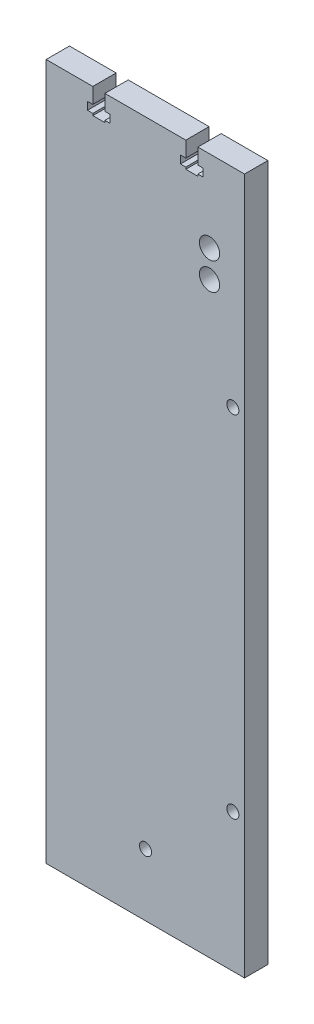
SolidWorks part; units mm, degrees
ref_plane "Płaszczyzna przednia" through (0, 0, 0) normal (0, 0, 1) x (1, 0, 0)
ref_plane "Płaszczyzna górna" through (0, 0, 0) normal (0, 1, 0) x (1, 0, 0)
ref_plane "Płaszczyzna prawa" through (0, 0, 0) normal (1, 0, 0) x (0, 0, -1)
sketch "Szkic1" plane through (0, 0, 0) normal (0, 0, 1) x (1, 0, 0)
  line L0 (23.5057, -200) -> (74.5057, -200)
  line L1 (23.5057, -200) -> (23.5057, -21)
  line L2 (74.5057, -200) -> (74.5057, -21)
  line L3 (23.5057, -21) -> (74.5057, -21)
  dimension "D2" = 51
  dimension "D3" = 179
extrude "Dodanie-wyciągnięcie1" add sketch "Szkic1" against normal blind 6
sketch "Szkic2" plane through (0, 0, -6) normal (0, 0, -1) x (-1, 0, 0)
  line L0 (-68.5057, -166) -> (-74.5057, -166) construction
  line L1 (-68.5057, -166) -> (-74.5057, -166)
  line L2 (-68.5057, -162.9) -> (-74.5057, -162.9) construction
  line L3 (-68.5057, -72.9) -> (-74.5057, -72.9) construction
  line L4 (-23.5057, -200) -> (-23.5057, -21)
  line L5 (-23.5057, -21) -> (-74.5057, -21)
  line L6 (-74.5057, -21) -> (-74.5057, -200)
  line L7 (-74.5057, -200) -> (-23.5057, -200)
  line L8 (-23.5057, -200) -> (-23.5057, -21)
  line L9 (-23.5057, -21) -> (-74.5057, -21)
  line L10 (-74.5057, -21) -> (-74.5057, -200)
  line L11 (-74.5057, -200) -> (-23.5057, -200)
  line L12 (-68.5057, -76) -> (-74.5057, -76) construction
  line L13 (-68.5057, -162.9) -> (-74.5057, -162.9)
  line L14 (-68.5057, -72.9) -> (-74.5057, -72.9)
  line L15 (-68.5057, -76) -> (-74.5057, -76)
  line L16 (-71.5057, -166) -> (-71.5057, -162.9)
  line L17 (-71.5057, -76) -> (-71.5057, -72.9)
  circle A0 centre (-71.5057, -74.45) radius 1.55
  circle A1 centre (-71.5057, -164.45) radius 1.55
  dimension "D2" = 3.1
  dimension "D3" = 3.1
  dimension "D1" = 0
sketch "Szkic3" plane through (0, 0, -6) normal (0, 0, -1) x (-1, 0, 0)
  circle A0 centre (-71.5057, -164.45) radius 1.55 construction
  circle A1 centre (-71.5057, -74.45) radius 1.55 construction
  circle A2 centre (-71.5057, -164.45) radius 1.55
  circle A3 centre (-71.5057, -74.45) radius 1.55
extrude "Wytnij-wyciągnięcie1" cut sketch "Szkic3" against normal through all
sketch "Szkic4" plane through (0, 0, -6) normal (0, 0, -1) x (-1, 0, 0)
  line L0 (-59.4057, -21) -> (-62.5057, -21)
  line L1 (-59.4057, -21) -> (-59.4057, -25)
  line L2 (-62.5057, -21) -> (-62.5057, -25)
  line L3 (-59.4057, -27.5) -> (-62.5057, -27.5)
  line L4 (-74.5057, -21) -> (-23.5057, -21) construction
  line L5 (-58.0307, -27) -> (-59.4057, -27)
  line L6 (-58.0307, -27) -> (-58.0307, -25)
  line L7 (-63.8807, -27) -> (-63.8807, -25)
  line L8 (-58.0307, -25) -> (-59.4057, -25)
  line L9 (-59.4057, -27) -> (-59.4057, -27.5)
  line L10 (-62.5057, -27) -> (-63.8807, -27)
  line L11 (-62.5057, -27) -> (-62.5057, -27.5)
  line L12 (-62.5057, -25) -> (-63.8807, -25)
  line L13 (-74.5057, -200) -> (-74.5057, -21) construction
  dimension "D1" = 5.85
  dimension "D2" = 6.5
  dimension "D3" = 1.375
  dimension "D4" = 3.1
  dimension "D5" = 2
  dimension "D6" = 0.5
  dimension "D7" = 12
extrude "Wytnij-wyciągnięcie2" cut sketch "Szkic4" against normal through all
pattern_linear "Szyk liniowy1" count 2 spacing 23.9 along (-1, 0, 0) of "Wytnij-wyciągnięcie2"
sketch "Szkic5" plane through (0, 0, -6) normal (0, 0, -1) x (-1, 0, 0)
  line L2 (-68.5057, -21) -> (-68.5057, -72.9) construction
  circle A0 centre (-65.5057, -42) radius 2.6
  circle A1 centre (-65.5057, -49) radius 2.6
  dimension "D1" = 7
  dimension "D2" = 5.2
  dimension "D3" = 5.2
  dimension "D4" = 0
  dimension "D5" = 3
extrude "Wytnij-wyciągnięcie3" cut sketch "Szkic5" against normal through all
sketch "Szkic6" plane through (0, 0, -6) normal (0, 0, -1) x (-1, 0, 0)
  line L0 (-47.5057, -181) -> (-47.5057, -187) construction
  line L1 (-50.6057, -181) -> (-50.6057, -187) construction
  line L2 (-47.5057, -181) -> (-47.5057, -187)
  line L3 (-50.6057, -181) -> (-50.6057, -187)
  line L4 (-50.6057, -184) -> (-47.5057, -184)
  circle A0 centre (-49.0557, -184) radius 1.55
sketch "Szkic7" plane through (0, 0, -6) normal (0, 0, -1) x (-1, 0, 0)
  circle A0 centre (-49.0557, -184) radius 1.55 construction
  circle A1 centre (-49.0557, -184) radius 1.55
extrude "Wytnij-wyciągnięcie4" cut sketch "Szkic7" against normal blind 6
equation "\"tolerancja_wpusy\"=0.2"
equation "\"dlugosc_wpustu_duzy\"=20"
equation "\"srednica_otworu_M3\"=3.1"
equation "\"szerokosc_nogi_T\"=3.1"
equation "\"dlugosc_T_30\"=11"
equation "\"grubosc_na_nakretke_kwadrat\"=2"
equation "\"szerokosc_na_nakretke_kwadrat\"=5.85"
equation "\"wyokosc_nadstawki_T\"=0.5"
equation "\"D2@Szkic2\"=\"srednica_otworu_M3\""
equation "\"D3@Szkic2\"=\"srednica_otworu_M3\""
equation "\"D1@Szkic4\"=\"szerokosc_na_nakretke_kwadrat\""
equation "\"dlugosc_T_20_6\"=14"
equation "\"D3@Szkic4\"=(\"szerokosc_na_nakretke_kwadrat\"-\"szerokosc_nogi_T\")/2"
equation "\"D4@Szkic4\"=\"szerokosc_nogi_T\""
equation "\"D5@Szkic4\"=\"grubosc_na_nakretke_kwadrat\""
equation "\"D6@Szkic4\"=\"wyokosc_nadstawki_T\""
